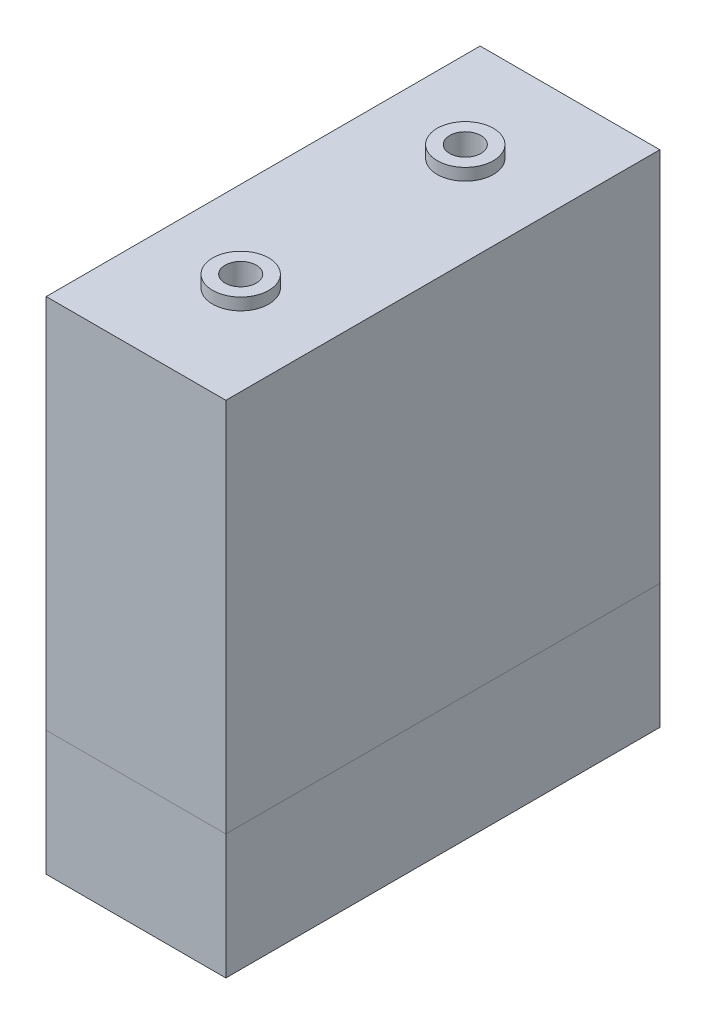
SolidWorks part; units mm, degrees
ref_plane "Front Plane" through (0, 0, 0) normal (0, 0, 1) x (1, 0, 0)
ref_plane "Top Plane" through (0, 0, 0) normal (0, 1, 0) x (1, 0, 0)
ref_plane "Right Plane" through (0, 0, 0) normal (1, 0, 0) x (0, 0, -1)
sketch "Sketch1" plane through (0, 0, 0) normal (0, 1, 0) x (1, 0, 0)
  line L1 (0, 0) -> (72, 0)
  line L2 (0, 0) -> (0, 173.9)
  line L3 (0, 173.9) -> (72, 173.9)
  line L4 (72, 0) -> (72, 173.9)
  dimension "D1" = 173.9
  dimension "D2" = 72
extrude "Boss-Extrude1" add sketch "Sketch1" along normal blind 200.5
sketch "Sketch2" plane through (0, 200.5, 0) normal (0, 1, 0) x (1, 0, 0)
  line L0 (36, 131.95) -> (36, 41.95) construction
  line L1 (0, 173.9) -> (0, 0) construction
  line L3 (0, 0) -> (72, 0) construction
  circle A0 centre (36, 131.95) radius 11.25
  circle A1 centre (36, 41.95) radius 11.25
  point P4 (36, 0)
  point P12 (0, 86.95)
  point P13 (36, 86.95)
  dimension "D1" = 90
  dimension "D2" = 22.5
extrude "Boss-Extrude2" add sketch "Sketch2" along normal blind 4.8
ref_plane "Plane1" through (0, 50, 0) normal (0, -1, 0) x (-1, 0, 0)
split "Split1" trim tools "Plane1" bodies to split 105 resulting bodies 111 112
sketch "Sketch6" plane through (0, 205.3, 0) normal (0, 1, 0) x (1, 0, 0)
  circle A7 centre (36, 131.95) radius 6.25
  circle A8 centre (36, 131.95) radius 6.25
  circle A10 centre (36, 41.95) radius 6.25
  circle A11 centre (36, 41.95) radius 6.25
  dimension "D1" = 5
  dimension "D2" = 5
extrude "Cut-Extrude1" cut sketch "Sketch6" against normal blind 10
